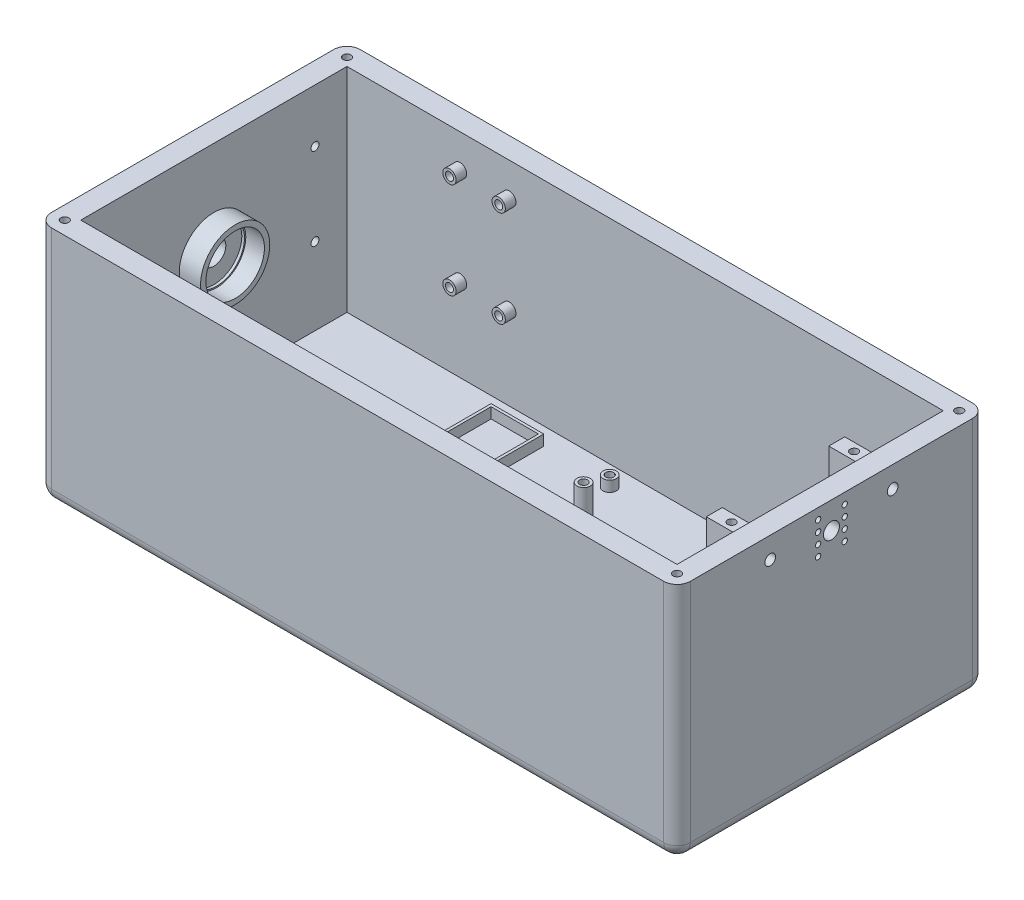
SolidWorks part; units mm, degrees
ref_plane "Front Plane" through (0, 0, 0) normal (0, 0, 1) x (1, 0, 0)
ref_plane "Top Plane" through (0, 0, 0) normal (0, 1, 0) x (1, 0, 0)
ref_plane "Right Plane" through (0, 0, 0) normal (1, 0, 0) x (0, 0, -1)
sketch "Sketch1" plane through (0, 0, 0) normal (0, 1, 0) x (1, 0, 0)
  line L1 (-120, 58) -> (120, 58)
  line L2 (-120, 58) -> (-120, -58)
  line L3 (-120, -58) -> (120, -58)
  line L4 (120, 58) -> (120, -58)
  line L5 (-120, 58) -> (120, -58) construction
  line L6 (-120, -58) -> (120, 58) construction
  point P0 (0, 0)
  dimension "D1" = 240
  dimension "D2" = 116
extrude "Boss-Extrude1" add sketch "Sketch1" along normal blind 10
sketch "Sketch2" plane through (0, 0, 0) normal (0, -1, 0) x (1, 0, 0)
  line L1 (-31.075, 31.075) -> (31.075, 31.075)
  line L2 (-31.075, 31.075) -> (-31.075, -31.075)
  line L3 (-31.075, -31.075) -> (31.075, -31.075)
  line L4 (31.075, 31.075) -> (31.075, -31.075)
  line L5 (-31.075, 31.075) -> (31.075, -31.075) construction
  line L6 (-31.075, -31.075) -> (31.075, 31.075) construction
  point P0 (0, 0)
  dimension "D1" = 62.15
  dimension "D2" = 62.15
extrude "Cut-Extrude1" cut sketch "Sketch2" against normal blind 2.5
sketch "Sketch3" plane through (0, 2.5, 0) normal (0, -1, 0) x (1, 0, 0)
  line L0 (0, 31.075) -> (0, -31.075) construction
  line L1 (31.075, 31.075) -> (-31.075, 31.075) construction
  line L2 (-31.075, -31.075) -> (31.075, -31.075) construction
  line L3 (-31.075, 0) -> (31.075, 0) construction
  line L4 (-31.075, 31.075) -> (-31.075, -31.075) construction
  line L5 (31.075, -31.075) -> (31.075, 31.075) construction
  line L6 (31.075, 31.075) -> (-31.075, 31.075) construction
  line L7 (-31.075, 31.075) -> (-31.075, -31.075) construction
  circle A0 centre (-26.075, 26.075) radius 1.5
  circle A1 centre (-26.075, -26.075) radius 1.5
  circle A2 centre (26.075, -26.075) radius 1.5
  circle A3 centre (26.075, 26.075) radius 1.5
  dimension "D1" = 3
  dimension "D3" = 5
  dimension "D2" = 5
extrude "Cut-Extrude2" cut sketch "Sketch3" against normal up to next
sketch "Sketch4" plane through (0, 0, 0) normal (0, -1, 0) x (1, 0, 0)
  line L0 (120, 58) -> (120, -58) construction
  line L1 (48, 7.75) -> (60, 7.75)
  line L2 (48, 7.75) -> (48, -7.75)
  line L3 (48, -7.75) -> (60, -7.75)
  line L4 (60, 7.75) -> (60, -7.75)
  line L5 (48, 7.75) -> (60, -7.75) construction
  line L6 (48, -7.75) -> (60, 7.75) construction
  point P0 (54, 0)
  dimension "D1" = 12
  dimension "D2" = 15.5
  dimension "D3" = 60
extrude "Cut-Extrude3" cut sketch "Sketch4" against normal blind 2.5
sketch "Sketch6" plane through (0, 2.5, 0) normal (0, -1, 0) x (1, 0, 0)
  line L0 (60, -7.75) -> (60, 7.75) construction
  line L1 (60, 7.75) -> (48, 7.75) construction
  line L2 (48, -7.75) -> (60, -7.75) construction
  circle A0 centre (58, 5.75) radius 1.5
  circle A1 centre (58, -5.75) radius 1.5
  dimension "D1" = 3
  dimension "D2" = 3
  dimension "D3" = 2
  dimension "D4" = 2
  dimension "D5" = 2
  dimension "D6" = 2
extrude "Cut-Extrude4" cut sketch "Sketch6" against normal up to next and the other way through all
sketch "Sketch7" plane through (0, 2.5, 0) normal (0, -1, 0) x (1, 0, 0)
  line L0 (48, -7.75) -> (60, -7.75) construction
  line L1 (48, 7.75) -> (54, 7.75)
  line L2 (48, 7.75) -> (48, -7.75)
  line L3 (48, -7.75) -> (54, -7.75)
  line L4 (54, 7.75) -> (54, -7.75)
extrude "Cut-Extrude5" cut sketch "Sketch7" against normal up to next
sketch "Sketch8" plane through (0, 10, 0) normal (0, 1, 0) x (1, 0, 0)
  line L1 (1.2, 26.7) -> (100, 26.7) construction
  line L2 (1.2, 26.7) -> (1.2, -26.7) construction
  line L3 (1.2, -26.7) -> (100, -26.7) construction
  line L4 (100, 26.7) -> (100, -26.7) construction
  line L5 (1.2, 26.7) -> (100, -26.7) construction
  line L6 (1.2, -26.7) -> (100, 26.7) construction
  line L11 (120, -58) -> (120, 58) construction
  line L15 (-120, -58) -> (120, -58) construction
  circle A0 centre (2.7, 24.2) radius 1.5
  circle A1 centre (9.7, -24.2) radius 1.5
  circle A2 centre (86.5, 24.2) radius 1.5
  circle A3 centre (84.5, -24.2) radius 1.5
  circle A4 centre (86.5, 24.2) radius 2.5
  circle A5 centre (84.5, -24.2) radius 2.3473
  circle A6 centre (9.7, -24.2) radius 2.5
  circle A7 centre (2.7, 24.2) radius 2.5
  point P0 (50.6, 0)
  dimension "D7" = 3
  dimension "D8" = 3
  dimension "D9" = 3
  dimension "D10" = 3
  dimension "D11" = 2.5
  dimension "D13" = 8.5
  dimension "D14" = 2.5
  dimension "D12" = 15.5
  dimension "D16" = 13.5
  dimension "D17" = 2.5
  dimension "D18" = 5
  dimension "D19" = 5
  dimension "D20" = 5
  dimension "D1" = 98.8
  dimension "D2" = 53.4
  dimension "D3" = 20
  dimension "D4" = 58
  dimension "D15" = 2.5
extrude "Boss-Extrude2" add sketch "Sketch8" along normal blind 15
sketch "Sketch9" plane through (0, 10, 0) normal (0, 1, 0) x (1, 0, 0)
  line L0 (-0.3, 58) -> (-0.3, -58) construction
  line L1 (-25.6, 47) -> (-4.3, 47) construction
  line L2 (-25.6, 47) -> (-25.6, 8.5) construction
  line L3 (-25.6, 8.5) -> (-4.3, 8.5) construction
  line L4 (-4.3, 47) -> (-4.3, 8.5) construction
  line L5 (-25.6, 47) -> (-4.3, 8.5) construction
  line L6 (-25.6, 8.5) -> (-4.3, 47) construction
  line L7 (-53.1, 47) -> (-29.6, 47) construction
  line L8 (-53.1, 47) -> (-53.1, 5) construction
  line L9 (-53.1, 5) -> (-29.6, 5) construction
  line L10 (-29.6, 47) -> (-29.6, 5) construction
  line L11 (-53.1, 47) -> (-29.6, 5) construction
  line L12 (-53.1, 5) -> (-29.6, 47) construction
  line L13 (120, 58) -> (-120, 58) construction
  line L14 (-120, -58) -> (120, -58) construction
  line L15 (-76.2, -9.5) -> (-54.9, -9.5) construction
  line L16 (-103.7, -9) -> (-80.2, -9) construction
  line L17 (-17.7, -47) -> (-17.7, -48)
  line L18 (-21.7, -23.8) -> (-4.3, -23.8)
  line L19 (-21.7, -23.8) -> (-21.7, -47)
  line L20 (-21.7, -47) -> (-17.7, -47)
  line L21 (-4.3, -23.8) -> (-4.3, -47)
  line L22 (-21.7, -23.8) -> (-4.3, -47) construction
  line L23 (-21.7, -47) -> (-4.3, -23.8) construction
  line L24 (-22.7, -22.8) -> (-3.3, -22.8)
  line L25 (-22.7, -22.8) -> (-22.7, -48)
  line L26 (-22.7, -48) -> (-17.7, -48)
  line L27 (-3.3, -22.8) -> (-3.3, -48)
  line L28 (-22.7, -22.8) -> (-3.3, -48) construction
  line L29 (-22.7, -48) -> (-3.3, -22.8) construction
  line L30 (-8.3, -47) -> (-8.3, -48)
  line L31 (-8.3, -47) -> (-4.3, -47)
  line L32 (-8.3, -48) -> (-3.3, -48)
  line L51 (-31.46, 43.383) -> (-31.46, 8.617)
  line L52 (-50.24, 42.383) -> (-32.46, 42.383)
  line L53 (-50.24, 42.383) -> (-50.24, 9.617)
  line L54 (-50.24, 9.617) -> (-32.46, 9.617)
  line L67 (31.45, 58) -> (31.45, -58) construction
  line L102 (-32.46, 42.383) -> (-32.46, 9.617)
  line L103 (-50.24, 42.383) -> (-32.46, 9.617) construction
  line L104 (-50.24, 9.617) -> (-32.46, 42.383) construction
  line L105 (-51.24, 8.617) -> (-31.46, 8.617)
  line L106 (-51.24, 43.383) -> (-51.24, 8.617)
  line L107 (-51.24, 43.383) -> (-31.46, 43.383)
  circle A0 centre (2.7, 24.2) radius 1.5 construction
  circle A1 centre (-5.8, 42.5) radius 1.5
  circle A2 centre (-5.8, 15.8) radius 1.5
  circle A3 centre (-24.1, 15.8) radius 1.5
  circle A4 centre (-24.1, 15.8) radius 2.5
  circle A5 centre (-5.8, 15.8) radius 2.5
  circle A6 centre (-5.8, 42.5) radius 2.5
  circle A7 centre (-50.6, 44.5) radius 1.5 construction
  circle A8 centre (-32.1, 44.5) radius 1.5 construction
  circle A9 centre (-32.1, 7.5) radius 1.5 construction
  circle A10 centre (-50.6, 7.5) radius 1.5 construction
  circle A11 centre (-50.6, 7.5) radius 2.5 construction
  circle A12 centre (-32.1, 7.5) radius 2.5 construction
  circle A13 centre (-32.1, 44.5) radius 2.5 construction
  circle A14 centre (-50.6, 44.5) radius 2.5 construction
  point P0 (-14.95, 27.75)
  point P5 (-41.35, 26)
  point P20 (-13, -35.4)
  point P27 (-13, -35.4)
  point P53 (-41.35, 26)
  dimension "D23" = 3
  dimension "D24" = 3
  dimension "D25" = 3
  dimension "D28" = 5
  dimension "D29" = 5
  dimension "D30" = 5
  dimension "D31" = 3
  dimension "D32" = 3
  dimension "D33" = 3
  dimension "D34" = 3
  dimension "D43" = 5
  dimension "D44" = 5
  dimension "D45" = 5
  dimension "D46" = 5
  dimension "D1" = 38.5
  dimension "D2" = 21.3
  dimension "D3" = 3
  dimension "D4" = 4
  dimension "D5" = 18
  dimension "D6" = 42
  dimension "D7" = 23.5
  dimension "D8" = 4
  dimension "D9" = 11
  dimension "D10" = 14
  dimension "D11" = 17.4
  dimension "D12" = 23.2
  dimension "D14" = 4
  dimension "D15" = 25.2
  dimension "D16" = 19.4
  dimension "D17" = 4
  dimension "D22" = 4.5
  dimension "D26" = 7.3
  dimension "D27" = 7.3
  dimension "D35" = 2.5
  dimension "D36" = 2.5
  dimension "D37" = 2.5
  dimension "D38" = 2.5
  dimension "D39" = 2.5
  dimension "D40" = 2.5
  dimension "D41" = 2.5
  dimension "D42" = 2.5
  dimension "D47" = 32.766
  dimension "D48" = 17.78
  dimension "D49" = 1
extrude "Boss-Extrude3" add sketch "Sketch9" along normal blind 4
sketch "Sketch10" plane through (0, 10, 0) normal (0, 1, 0) x (1, 0, 0)
  line L0 (-112, 50) -> (112, 50)
  line L1 (-120, 58) -> (120, 58)
  line L2 (-120, 58) -> (-120, -58)
  line L3 (-120, -58) -> (120, -58)
  line L4 (120, 58) -> (120, -58)
  line L5 (-120, 58) -> (120, -58) construction
  line L6 (-120, -58) -> (120, 58) construction
  line L7 (112, 50) -> (112, -50)
  line L8 (-112, -50) -> (112, -50)
  line L9 (-112, 50) -> (-112, -50)
  point P0 (0, 0)
  dimension "D1" = 8
extrude "Boss-Extrude4" add sketch "Sketch10" along normal blind 80
sketch "Sketch11" plane through (112, 0, 0) normal (-1, 0, 0) x (0, 0, 1)
  line L0 (-50, 90) -> (-50, 10) construction
  line L1 (-37, 82.5) -> (23, 82.5) construction
  line L2 (-37, 82.5) -> (-37, 17.5) construction
  line L3 (-37, 17.5) -> (23, 17.5) construction
  line L4 (23, 82.5) -> (23, 17.5) construction
  line L5 (-37, 82.5) -> (23, 17.5) construction
  line L6 (-37, 17.5) -> (23, 82.5) construction
  line L7 (-27.9, 70.9) -> (13.9, 70.9) construction
  line L8 (-27.9, 70.9) -> (-27.9, 29.1) construction
  line L9 (-27.9, 29.1) -> (13.9, 29.1) construction
  line L10 (13.9, 70.9) -> (13.9, 29.1) construction
  line L11 (-27.9, 70.9) -> (13.9, 29.1) construction
  line L12 (-27.9, 29.1) -> (13.9, 70.9) construction
  line L15 (50, 90) -> (-50, 90) construction
  circle A0 centre (-22.9, 65.9) radius 1.5
  circle A1 centre (8.9, 65.9) radius 1.5
  circle A2 centre (8.9, 34.1) radius 1.5
  circle A3 centre (-22.9, 34.1) radius 1.5
  circle A4 centre (-7, 67.5) radius 4.5
  point P0 (-7, 50)
  point P6 (-7, 50)
  dimension "D5" = 3
  dimension "D6" = 3
  dimension "D8" = 3
  dimension "D7" = 3
  dimension "D19" = 9
  dimension "D1" = 65
  dimension "D2" = 60
  dimension "D3" = 41.8
  dimension "D4" = 41.8
  dimension "D10" = 5
  dimension "D11" = 5
  dimension "D12" = 5
  dimension "D13" = 5
  dimension "D14" = 5
  dimension "D15" = 5
  dimension "D16" = 5
  dimension "D17" = 43
  dimension "D18" = 40
  dimension "D20" = 15
  dimension "D21" = 30
  dimension "D9" = 5
extrude "Cut-Extrude6" [suppressed] cut sketch "Sketch11" against normal up to next contours A1 | A3 | A2 | A0
sketch "Sketch13" [suppressed] plane through (120, 0, 0) normal (1, 0, 0) x (0, 0, -1)
  circle A0 centre (-8.9, 65.9) radius 3
  circle A1 centre (22.9, 65.9) radius 3
  circle A2 centre (22.9, 34.1) radius 3
  circle A3 centre (-8.9, 34.1) radius 3
  dimension "D1" = 6
  dimension "D2" = 6
  dimension "D3" = 6
  dimension "D4" = 6
extrude "Cut-Extrude7" [suppressed] cut sketch "Sketch13" against normal blind 4
sketch "Sketch24" plane through (-112, 0, 0) normal (1, 0, 0) x (0, 0, -1)
  line L0 (50, 10) -> (-50, 10) construction
  line L1 (-43, 34) -> (43, 34) construction
  line L2 (-43, 34) -> (-43, 75) construction
  line L3 (-43, 75) -> (43, 75) construction
  line L4 (43, 34) -> (43, 75) construction
  line L5 (-43, 34) -> (43, 75) construction
  line L6 (-43, 75) -> (43, 34) construction
  line L7 (50, 90) -> (-50, 90) construction
  line L8 (0, 75) -> (0, 34) construction
  circle A0 centre (-38, 70) radius 1.5
  circle A1 centre (-38, 39) radius 1.5
  circle A2 centre (38, 39) radius 1.5
  circle A3 centre (38, 70) radius 1.5
  point P0 (0, 54.5)
  point P9 (0, 10)
  dimension "D4" = 3
  dimension "D5" = 3
  dimension "D6" = 5
  dimension "D7" = 5
  dimension "D8" = 5
  dimension "D9" = 5
  dimension "D1" = 86
  dimension "D2" = 41
  dimension "D3" = 15
extrude "Cut-Extrude14" cut sketch "Sketch24" against normal up to next
sketch "Sketch14" plane through (-112, 0, 0) normal (1, 0, 0) x (0, 0, -1)
  circle A0 centre (0, 54.5) radius 13
  circle A2 centre (0, 54.5) radius 11
  dimension "D1" = 26
  dimension "D2" = 22
  dimension "D3" = 0
extrude "Boss-Extrude6" add sketch "Sketch14" along normal blind 8
sketch "Sketch16" plane through (-112, 0, 0) normal (1, 0, 0) x (0, 0, -1)
  circle A0 centre (0, 54.5) radius 10.5
  circle A1 centre (0, 54.5) radius 11
  dimension "D1" = 21
  dimension "D2" = 22
extrude "Boss-Extrude7" add sketch "Sketch16" along normal blind 1
sketch "Sketch18" plane through (0, 0, -50) normal (0, 0, 1) x (1, 0, 0)
  line L0 (-60.25, 80) -> (-60.25, 38) construction
  line L1 (-72, 80) -> (-48.5, 80) construction
  line L2 (-72, 80) -> (-72, 38) construction
  line L3 (-72, 38) -> (-48.5, 38) construction
  line L4 (-48.5, 80) -> (-48.5, 38) construction
  line L5 (-72, 80) -> (-48.5, 38) construction
  line L6 (-72, 38) -> (-48.5, 80) construction
  line L7 (-72, 59.4256) -> (-48.5, 59.4256) construction
  line L8 (112, 90) -> (-112, 90) construction
  line L9 (-112, 90) -> (-112, 10) construction
  circle A0 centre (-69.5, 77.5) radius 1.5
  circle A1 centre (-69.5, 77.5) radius 2.5
  circle A2 centre (-69.5, 41.3512) radius 1.5
  circle A3 centre (-69.5, 41.3512) radius 2.5
  circle A4 centre (-51, 41.3512) radius 2.5
  circle A5 centre (-51, 41.3512) radius 1.5
  circle A6 centre (-51, 77.5) radius 2.5
  circle A7 centre (-51, 77.5) radius 1.5
  point P0 (-60.25, 59)
  dimension "D3" = 3
  dimension "D4" = 5
  dimension "D5" = 2.5
  dimension "D6" = 2.5
  dimension "D1" = 42
  dimension "D2" = 23.5
  dimension "D7" = 10
  dimension "D8" = 40
sketch "Sketch17" plane through (-112, 0, 0) normal (1, 0, 0) x (0, 0, -1)
  circle A0 centre (0, 54.5) radius 4.5
  dimension "D1" = 9
extrude "Cut-Extrude9" cut sketch "Sketch17" against normal up to next
extrude "Boss-Extrude8" add sketch "Sketch18" along normal blind 4
fillet "Fillet1" radius 5 8 edges at (120, 45, -58) (-120, 45, -58) (0, 0, -58) (-120, 0, 0) (0, 0, 58) (-120, 45, 58) (120, 0, 0) (120, 45, 58)
sketch "Sketch19" plane through (0, 90, 0) normal (0, 1, 0) x (1, 0, 0)
  circle A3 centre (115, 53) radius 1.5
  circle A4 centre (-115, 53) radius 1.5
  circle A5 centre (-115, -53) radius 1.5
  circle A6 centre (115, -53) radius 1.5
  dimension "D1" = 3
  dimension "D2" = 3
  dimension "D3" = 3
  dimension "D4" = 3
extrude "Cut-Extrude10" cut sketch "Sketch19" against normal blind 20
sketch "Sketch20" plane through (120, 0, 0) normal (1, 0, 0) x (0, 0, -1)
  line L0 (0, 90) -> (0, 0) construction
  line L1 (-53, 90) -> (53, 90) construction
  circle A0 centre (-23, 82) radius 2
  circle A1 centre (23, 82) radius 2
  dimension "D1" = 23
  dimension "D2" = 4
  dimension "D3" = 8
extrude "Cut-Extrude11" cut sketch "Sketch20" against normal up to next
sketch "Sketch21" plane through (112, 0, 0) normal (-1, 0, 0) x (0, 0, 1)
  line L1 (-26, 87) -> (-20, 87)
  line L2 (-26, 87) -> (-26, 77)
  line L3 (-26, 77) -> (-20, 77)
  line L4 (-20, 87) -> (-20, 77)
  line L5 (-26, 87) -> (-20, 77) construction
  line L6 (-26, 77) -> (-20, 87) construction
  line L7 (20, 87) -> (26, 87)
  line L8 (20, 87) -> (20, 77)
  line L9 (20, 77) -> (26, 77)
  line L10 (26, 87) -> (26, 77)
  line L11 (20, 87) -> (26, 77) construction
  line L12 (20, 77) -> (26, 87) construction
  circle A0 centre (23, 82) radius 2
  circle A1 centre (-23, 82) radius 2
  point P0 (-23, 82)
  point P6 (23, 82)
  dimension "D5" = 4
  dimension "D6" = 4
  dimension "D1" = 6
  dimension "D2" = 6
  dimension "D3" = 10
  dimension "D4" = 10
extrude "Boss-Extrude9" add sketch "Sketch21" along normal blind 13
sketch "Sketch22" plane through (0, 87, 0) normal (0, 1, 0) x (1, 0, 0)
  line L0 (99, -26) -> (99, -20) construction
  line L1 (99, -20) -> (112, -20) construction
  line L2 (99, 20) -> (99, 26) construction
  line L3 (99, 26) -> (112, 26) construction
  circle A0 centre (105.5, -23) radius 1.5
  circle A1 centre (105.5, 23) radius 1.5
  dimension "D1" = 3
  dimension "D2" = 6.5
  dimension "D3" = 3
  dimension "D4" = 3
  dimension "D5" = 6.5
  dimension "D6" = 3
extrude "Cut-Extrude12" cut sketch "Sketch22" against normal up to next
sketch "Sketch23" plane through (120, 0, 0) normal (1, 0, 0) x (0, 0, -1)
  line L0 (0, 90) -> (0, 5) construction
  line L1 (-53, 90) -> (53, 90) construction
  line L2 (-53, 5) -> (53, 5) construction
  line L3 (-9.0972, 80) -> (9.0972, 80) construction
  circle A0 centre (5, 78) radius 1
  circle A1 centre (-5, 78) radius 1
  circle A2 centre (5, 74) radius 1
  circle A3 centre (-5, 74) radius 1
  circle A4 centre (-5, 86) radius 1
  circle A5 centre (5, 86) radius 1
  circle A6 centre (-5, 82) radius 1
  circle A7 centre (5, 82) radius 1
  circle A8 centre (0, 80) radius 3
  point P24 (0, 80)
  dimension "D1" = 2
  dimension "D2" = 2
  dimension "D3" = 5
  dimension "D4" = 5
  dimension "D5" = 12
  dimension "D6" = 12
  dimension "D7" = 2
  dimension "D8" = 2
  dimension "D9" = 5
  dimension "D10" = 5
  dimension "D11" = 4
  dimension "D12" = 4
  dimension "D13" = 2
  dimension "D14" = 6
extrude "Cut-Extrude13" cut sketch "Sketch23" against normal up to next
equation "\"D2@Sketch2\"=\"D1@Sketch2\""
equation "\"D15@Sketch9\"=\"D12@Sketch9\"+2"
equation "\"D16@Sketch9\"=\"D11@Sketch9\"+2"
equation "\"D17@Sketch11\"=86/2"
equation "\"D18@Sketch11\"=80/2"
